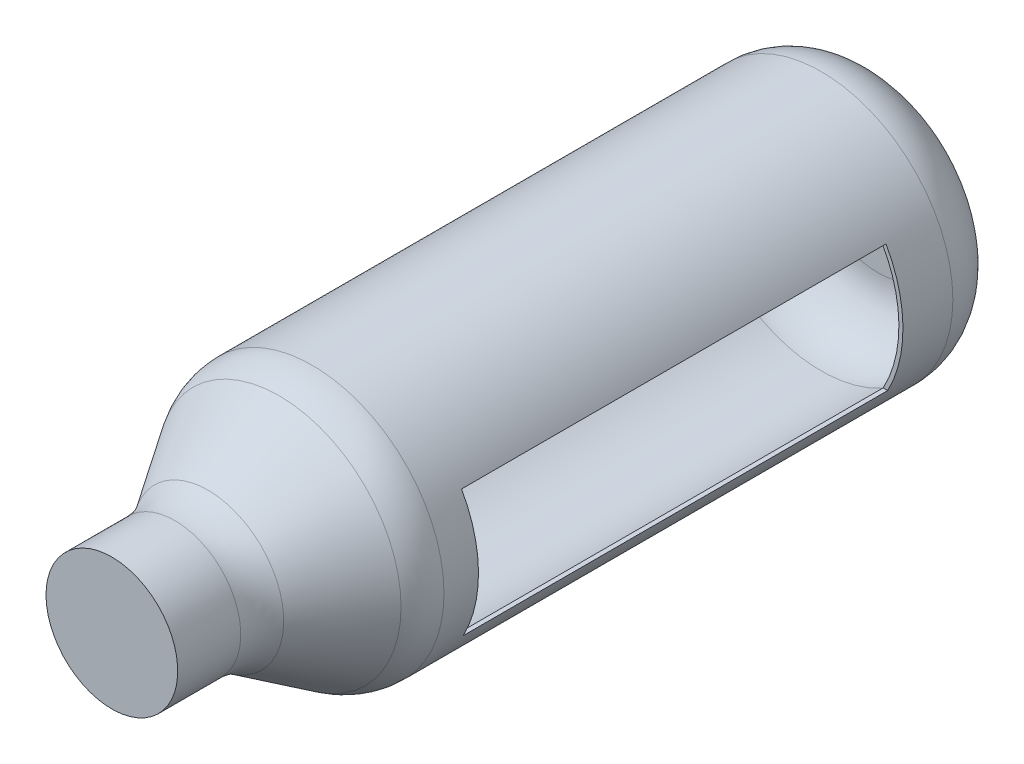
SolidWorks part; units mm, degrees
ref_plane "Front Plane" through (0, 0, 0) normal (1, 0, 0) x (0, 1, 0)
ref_plane "Top Plane" through (0, 0, 0) normal (0, 0, 1) x (0, 1, 0)
ref_plane "Right Plane" through (0, 0, 0) normal (0, 1, 0) x (-1, 0, 0)
sketch "Sketch1" plane through (0, 0, 0) normal (1, 0, 0) x (0, 1, 0)
  line L0 (0, 0) -> (17.5, 0)
  line L1 (0, 0) -> (0, 190) construction
  line L2 (32.5, 15) -> (32.5, 140.5534)
  line L3 (30.0767, 148.7282) -> (18.6733, 166.2718)
  line L4 (16.25, 174.4466) -> (16.25, 190)
  line L5 (16.25, 190) -> (0, 190)
  line L6 (0, 1) -> (17.5, 1)
  line L7 (31.5, 15) -> (31.5, 140.5534)
  line L8 (29.2382, 148.1832) -> (17.8349, 165.7268)
  line L9 (15.25, 174.4466) -> (15.25, 189)
  line L10 (15.25, 189) -> (0, 189)
  line L11 (0, 0) -> (0, 1)
  line L12 (0, 189) -> (0, 190)
  arc A0 (18.6733, 166.2718) -> (16.25, 174.4466) centre (31.25, 174.4466) cw
  arc A1 (32.5, 140.5534) -> (30.0767, 148.7282) centre (17.5, 140.5534) ccw
  arc A2 (17.5, 0) -> (32.5, 15) centre (17.5, 15) ccw
  arc A3 (17.5, 1) -> (31.5, 15) centre (17.5, 15) ccw
  arc A4 (31.5, 140.5534) -> (29.2382, 148.1832) centre (17.5, 140.5534) ccw
  arc A5 (17.8349, 165.7268) -> (15.25, 174.4466) centre (31.25, 174.4466) cw
  point P10 (16.25, 170)
  point P13 (32.5, 145)
  point P16 (32.5, 0)
  dimension "D5" = 15
  dimension "D1" = 65
  dimension "D2" = 145
  dimension "D3" = 190
  dimension "D4" = 20
  dimension "D6" = 1
revolve "Revolve1" add sketch "Sketch1" angle 360 about L1
ref_plane "Plane1" through (60, 0, 0) normal (1, 0, 0) x (0, 1, 0)
sketch "Sketch2" plane through (60, 0, 0) normal (1, 0, 0) x (0, 1, 0)
  line L1 (-15.1607, 132.0404) -> (15.954, 132.0404)
  line L2 (-15.1607, 132.0404) -> (-15.1607, 27.3087)
  line L3 (-15.1607, 27.3087) -> (15.954, 27.3087)
  line L4 (15.954, 132.0404) -> (15.954, 27.3087)
extrude "Cut-Extrude1" cut sketch "Sketch2" against normal blind 48
